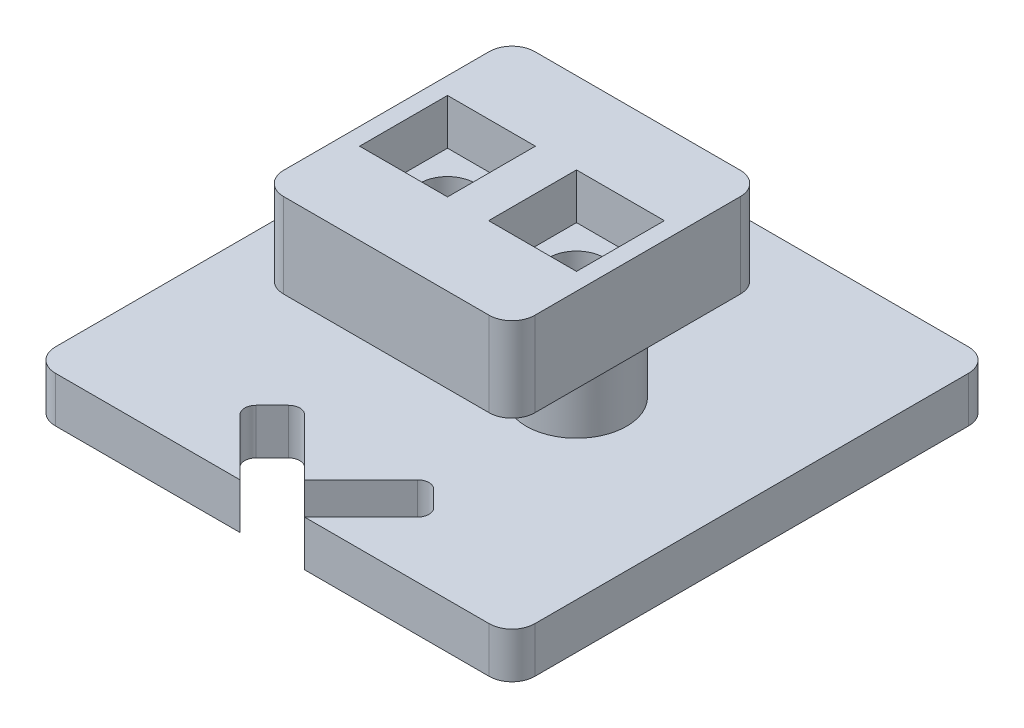
SolidWorks part; units mm, degrees
ref_plane "Front Plane" through (0, 0, 0) normal (0, 0, 1) x (1, 0, 0)
ref_plane "Top Plane" through (0, 0, 0) normal (0, 1, 0) x (1, 0, 0)
ref_plane "Right Plane" through (0, 0, 0) normal (1, 0, 0) x (0, 0, -1)
sketch "Sketch1" plane through (0, 0, 0) normal (0, 1, 0) x (1, 0, 0)
  line L1 (-5.5, -5.5) -> (5.5, -5.5)
  line L2 (-5.5, -5.5) -> (-5.5, 5.5)
  line L3 (-5.5, 5.5) -> (5.5, 5.5)
  line L4 (5.5, -5.5) -> (5.5, 5.5)
  line L5 (-5.5, -5.5) -> (5.5, 5.5) construction
  line L6 (-5.5, 5.5) -> (5.5, -5.5) construction
  point P0 (0, 0)
  dimension "D1" = 11
  dimension "D2" = 11
extrude "Boss-Extrude1" add sketch "Sketch1" along normal blind 3.7
fillet "Fillet1" radius 1 4 edges at (-5.5, 1.85, -5.5) (-5.5, 1.85, 5.5) (5.5, 1.85, -5.5) (5.5, 1.85, 5.5)
sketch "Sketch2" plane through (0, 3.7, 0) normal (0, 1, 0) x (1, 0, 0)
  line L0 (-2.825, 0) -> (2.825, 0) construction
  line L2 (-4.75, -1.925) -> (-0.9, -1.925)
  line L3 (-4.75, -1.925) -> (-4.75, 1.925)
  line L4 (-4.75, 1.925) -> (-0.9, 1.925)
  line L5 (-0.9, -1.925) -> (-0.9, 1.925)
  line L6 (-4.75, -1.925) -> (-0.9, 1.925) construction
  line L7 (-4.75, 1.925) -> (-0.9, -1.925) construction
  line L8 (0.9, -1.925) -> (4.75, -1.925)
  line L9 (0.9, -1.925) -> (0.9, 1.925)
  line L10 (0.9, 1.925) -> (4.75, 1.925)
  line L11 (4.75, -1.925) -> (4.75, 1.925)
  line L12 (0.9, -1.925) -> (4.75, 1.925) construction
  line L13 (0.9, 1.925) -> (4.75, -1.925) construction
  point P4 (0, 0)
  dimension "D1" = 3.85
  dimension "D2" = 3.85
  dimension "D3" = 3.85
  dimension "D4" = 3.85
  dimension "D5" = 5.65
extrude "Cut-Extrude1" cut sketch "Sketch2" against normal blind 2
sketch "Sketch4" plane through (0, 0, 0) normal (0, -1, 0) x (-1, 0, 0)
  line L0 (2.825, 0) -> (-2.825, 0) construction
  circle A0 centre (2.825, 0) radius 2.2
  circle A1 centre (-2.825, 0) radius 2.2
  point P8 (0, 0)
  dimension "D1" = 5.65
  dimension "D2" = 4.4
  dimension "D3" = 4.4
extrude "Boss-Extrude2" add sketch "Sketch4" along normal blind 5
sketch "Sketch5" plane through (0, -5, 0) normal (0, -1, 0) x (-1, 0, 0)
  line L1 (9.5, 10.5) -> (-9.5, 10.5)
  line L2 (10.5, 9.5) -> (10.5, -9.5)
  line L3 (9.5, -10.5) -> (-9.5, -10.5)
  line L4 (-10.5, 9.5) -> (-10.5, -9.5)
  line L5 (10.5, 10.5) -> (-10.5, -10.5) construction
  line L6 (10.5, -10.5) -> (-10.5, 10.5) construction
  arc A0 (10.5, -9.5) -> (9.5, -10.5) centre (9.5, -9.5) cw
  arc A1 (-10.5, -9.5) -> (-9.5, -10.5) centre (-9.5, -9.5) ccw
  arc A2 (-9.5, 10.5) -> (-10.5, 9.5) centre (-9.5, 9.5) ccw
  arc A3 (9.5, 10.5) -> (10.5, 9.5) centre (9.5, 9.5) cw
  point P0 (0, 0)
  dimension "D3" = 1
  dimension "D1" = 21
  dimension "D2" = 21
extrude "Boss-Extrude3" add sketch "Sketch5" against normal blind 2
sketch "Sketch3" plane through (0, 3.7, 0) normal (0, 1, 0) x (1, 0, 0)
  line L0 (-2.825, 0) -> (2.825, 0) construction
  circle A0 centre (-2.825, 0) radius 1.2
  circle A1 centre (2.825, 0) radius 1.2
  point P8 (0, 0)
  dimension "D2" = 2.4
  dimension "D3" = 2.4
  dimension "D1" = 5.65
extrude "Cut-Extrude2" cut sketch "Sketch3" against normal through all
sketch "Sketch7" plane through (0, -3, 0) normal (0, 1, 0) x (1, 0, 0)
  line L0 (9.5, -10.5) -> (-9.5, -10.5) construction
  line L1 (2.8284, -14.7426) -> (4.2426, -13.3284)
  line L2 (2.8284, -14.7426) -> (-3.8891, -8.0251)
  line L3 (-3.8891, -7.318) -> (-3.182, -6.6109)
  line L4 (4.2426, -13.3284) -> (-2.4749, -6.6109)
  line L5 (2.8284, -14.7426) -> (-2.8284, -6.2574) construction
  line L6 (-4.2426, -7.6716) -> (4.2426, -13.3284) construction
  line L8 (-4.2426, -13.3284) -> (-2.8284, -14.7426)
  line L9 (-4.2426, -13.3284) -> (2.4749, -6.6109)
  line L10 (3.182, -6.6109) -> (3.8891, -7.318)
  line L11 (-2.8284, -14.7426) -> (3.8891, -8.0251)
  line L12 (-4.2426, -13.3284) -> (4.2426, -7.6716) construction
  line L13 (2.8284, -6.2574) -> (-2.8284, -14.7426) construction
  arc A0 (-2.4749, -6.6109) -> (-3.182, -6.6109) centre (-2.8284, -6.9645) ccw
  arc A1 (3.8891, -7.318) -> (3.8891, -8.0251) centre (3.5355, -7.6716) cw
  arc A2 (3.182, -6.6109) -> (2.4749, -6.6109) centre (2.8284, -6.9645) ccw
  arc A3 (-3.8891, -7.318) -> (-3.8891, -8.0251) centre (-3.5355, -7.6716) ccw
  point P0 (0, -10.5)
  point P7 (0, -10.5)
  point P12 (-1.4142, -10.5)
  point P13 (1.4142, -10.5)
  line M12 (-9.5, -10.5) -> (9.5, -10.5)
  dimension "D7" = 0.5
  dimension "D8" = 0.5
  dimension "D1" = 2
  dimension "D2" = 45
  dimension "D3" = 2
  dimension "D4" = 45
  dimension "D5" = 4
  dimension "D6" = 4
extrude "Cut-Extrude3" cut sketch "Sketch7" against normal through all contours L10 A2 L9 L4 L11 A1 | L3 A3 L2 L9 L4 A0 | L9 L4 M12
sketch "Sketch8" plane through (0, -5, 0) normal (0, -1, 0) x (1, 0, 0)
  circle A0 centre (-2.825, 0) radius 1.2
  circle A1 centre (-2.825, 0) radius 2.2
  circle A2 centre (2.825, 0) radius 1.2
  circle A3 centre (2.825, 0) radius 2.2
  dimension "D1" = 1
  dimension "D2" = 1
extrude "Boss-Extrude4" add sketch "Sketch8" along normal blind 4
equation "\"D2@Sketch2\"=\"D1@Sketch2\""
equation "\"D3@Sketch2\"=\"D1@Sketch2\""
equation "\"D4@Sketch2\"=\"D1@Sketch2\""
equation "\"D2@Sketch1\"=\"D1@Sketch1\""
equation "\"D3@Sketch3\"=\"D2@Sketch3\""
equation "\"D3@Sketch4\"=\"D2@Sketch4\""
equation "\"D2@Sketch5\"=\"D1@Sketch5\""
equation "\"D3@Sketch7\"=\"D1@Sketch7\""
equation "\"D6@Sketch7\"=\"D5@Sketch7\""
equation "\"D2@Sketch8\"=\"D1@Sketch8\""
